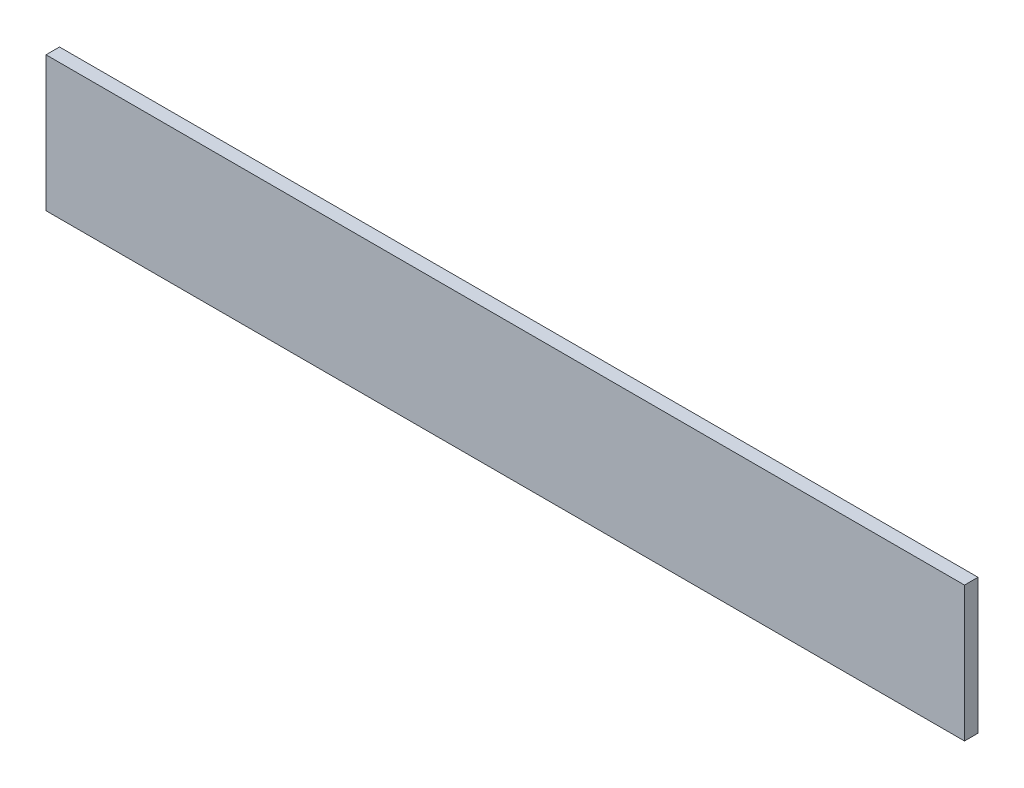
SolidWorks part; units mm, degrees
material "Balsa"
ref_plane "Plan de face" through (0, 0, 0) normal (0, 0, 1) x (1, 0, 0)
ref_plane "Plan de dessus" through (0, 0, 0) normal (0, 1, 0) x (1, 0, 0)
ref_plane "Plan de droite" through (0, 0, 0) normal (1, 0, 0) x (0, 0, -1)
sketch "Esquisse1" plane through (0, 0, 0) normal (0, 0, 1) x (1, 0, 0)
  line L1 (0, 0) -> (-680, 0)
  line L2 (0, 0) -> (0, 100)
  line L3 (0, 100) -> (-680, 100)
  line L4 (-680, 0) -> (-680, 100)
  dimension "D1" = 680
  dimension "D2" = 100
extrude "Boss.-Extru.1" add sketch "Esquisse1" along normal blind 10
